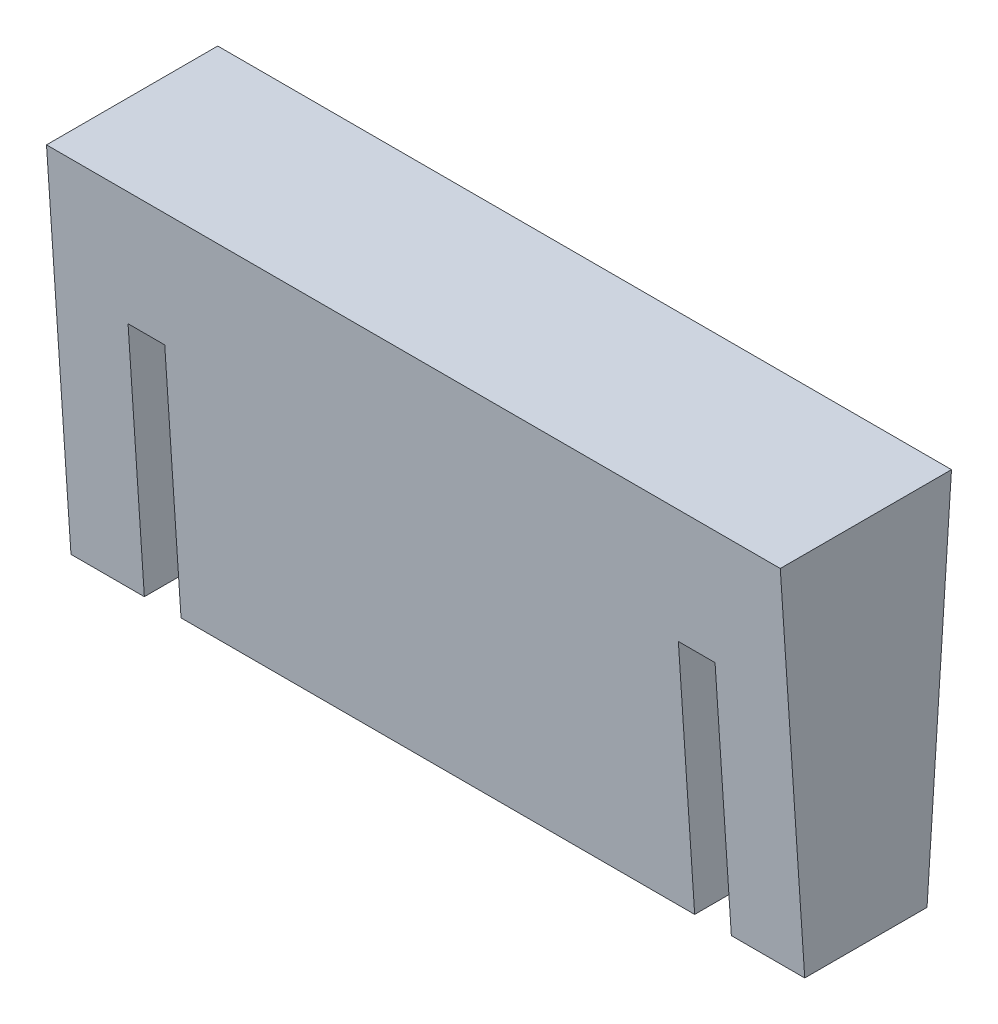
SolidWorks part; units mm, degrees
ref_plane "Front Plane" through (0, 0, 0) normal (0, 0, 1) x (1, 0, 0)
ref_plane "Top Plane" through (0, 0, 0) normal (0, 1, 0) x (1, 0, 0)
ref_plane "Right Plane" through (0, 0, 0) normal (1, 0, 0) x (0, 0, -1)
sketch "Sketch1" plane through (0, 0, 0) normal (0, 1, 0) x (1, 0, 0)
  line L0 (-13.0337, 0) -> (18.4045, 0) construction
  line L1 (0, 9.3483) -> (0, -8.4944) construction
  line L2 (-30, 7) -> (30, 7)
  line L3 (-30, 7) -> (-30, -7)
  line L4 (-30, -7) -> (30, -7)
  line L5 (30, 7) -> (30, -7)
  line L6 (-30, 7) -> (30, -7) construction
  line L7 (-30, -7) -> (30, 7) construction
  point P3 (0, 0)
  dimension "D1" = 60
  dimension "D2" = 14
extrude "Boss-Extrude1" add sketch "Sketch1" along normal blind 30
sketch "Sketch2" plane through (0, 0, 7) normal (0, 0, 1) x (1, 0, 0)
  line L0 (0, 33.6752) -> (0, -10.248) construction
  line L1 (-30, 0) -> (30, 0) construction
  line L2 (-24, 0) -> (-21, 0)
  line L3 (-24, 0) -> (-24, 20)
  line L4 (-24, 20) -> (-21, 20)
  line L5 (-21, 0) -> (-21, 20)
  line L6 (24, 0) -> (21, 0)
  line L7 (24, 20) -> (21, 20)
  line L8 (24, 0) -> (24, 20)
  line L9 (21, 0) -> (21, 20)
  dimension "D1" = 3
  dimension "D2" = 21
  dimension "D3" = 20
extrude "Cut-Extrude1" cut sketch "Sketch2" against normal through all
sketch "Sketch3" plane through (-30, 0, 0) normal (-1, 0, 0) x (0, 0, 1)
  line L0 (0, 34.2759) -> (0, -8.4095) construction
  line L1 (-7, 30) -> (-5, 0)
  line L2 (-7, 0) -> (7, 0) construction
  line L3 (7, 30) -> (5, 0)
  line L4 (-5, 0) -> (-7, 0)
  line L5 (-7, 0) -> (-7, 30)
  line L6 (5, 0) -> (7, 0)
  line L7 (7, 0) -> (7, 30)
  dimension "D1" = 2
extrude "Cut-Extrude2" cut sketch "Sketch3" against normal through all
